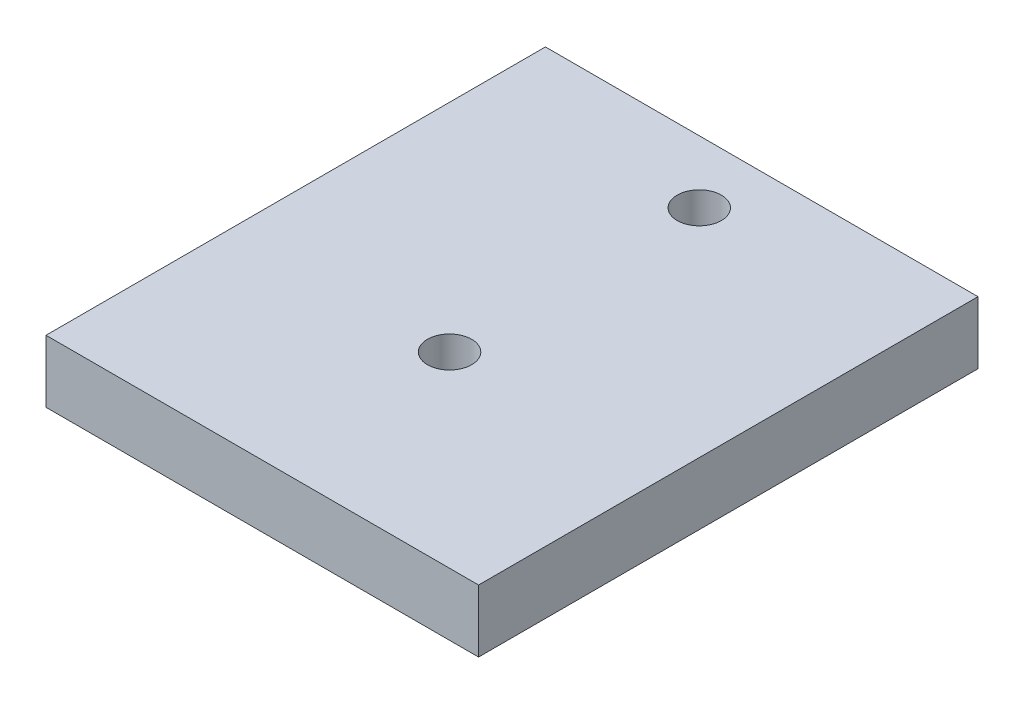
SolidWorks part; units mm, degrees
ref_plane "Front Plane" through (0, 0, 0) normal (0, 0, 1) x (1, 0, 0)
ref_plane "Top Plane" through (0, 0, 0) normal (0, 1, 0) x (1, 0, 0)
ref_plane "Right Plane" through (0, 0, 0) normal (1, 0, 0) x (0, 0, -1)
sketch "Sketch1" plane through (0, 0, 0) normal (0, 1, 0) x (1, 0, 0)
  line L1 (-22, -25.4) -> (22, -25.4)
  line L2 (-22, -25.4) -> (-22, 25.4)
  line L3 (-22, 25.4) -> (22, 25.4)
  line L4 (22, -25.4) -> (22, 25.4)
  line L5 (-22, -25.4) -> (22, 25.4) construction
  line L6 (-22, 25.4) -> (22, -25.4) construction
  point P0 (0, 0)
  dimension "D1" = 50.8
  dimension "D2" = 44
extrude "Boss-Extrude1" add sketch "Sketch1" along normal blind 6.35
sketch "Sketch2" plane through (0, 6.35, 0) normal (0, 1, 0) x (1, 0, 0)
  circle A1 centre (0, 19.05) radius 2.2479
  circle A2 centre (0, -6.35) radius 2.2479
  dimension "D1" = 19.05
  dimension "D3" = 4.4958
  dimension "D2" = 4.4958
extrude "Cut-Extrude1" cut sketch "Sketch2" against normal through all
